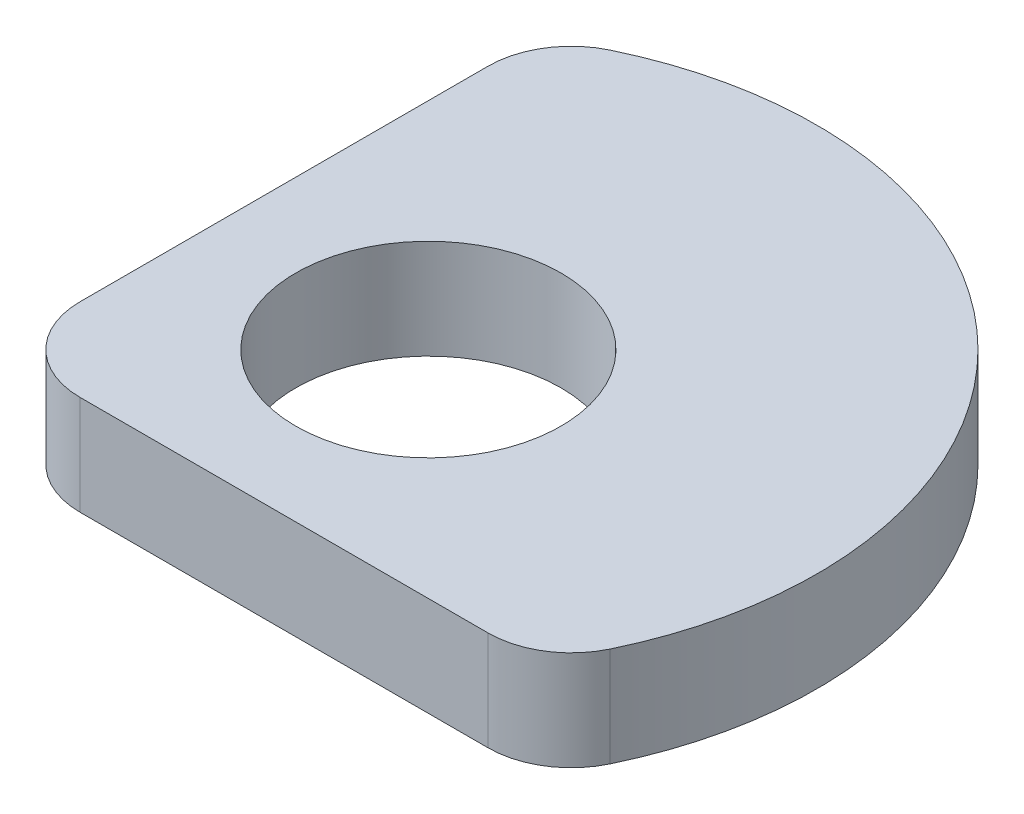
SolidWorks part; units mm, degrees
ref_plane "Front Plane" through (0, 0, 0) normal (0, 0, 1) x (1, 0, 0)
ref_plane "Top Plane" through (0, 0, 0) normal (0, 1, 0) x (1, 0, 0)
ref_plane "Right Plane" through (0, 0, 0) normal (1, 0, 0) x (0, 0, -1)
sketch "Sketch1" plane through (0, 0, 0) normal (0, 1, 0) x (1, 0, 0)
  line L0 (0, 0) -> (6.5, 0)
  line L1 (0, 0) -> (0, 6.5)
  line L2 (2.6, 0) -> (2.6, 2.6) construction
  line L3 (2.6, 2.6) -> (0, 2.6) construction
  circle A0 centre (2.6, 2.6) radius 1.6
  arc A1 (0, 6.5) -> (6.5, 0) centre (2.6, 2.6) cw
  point P9 (0, 0)
  dimension "D3" = 3.2
  dimension "D1" = 6.5
  dimension "D2" = 2.6
extrude "Boss-Extrude1" add sketch "Sketch1" along normal blind 1.2
fillet "Fillet1" radius 1 3 edges at (0, 0.6, -6.5) (0, 0.6, 0) (6.5, 0.6, 0)
